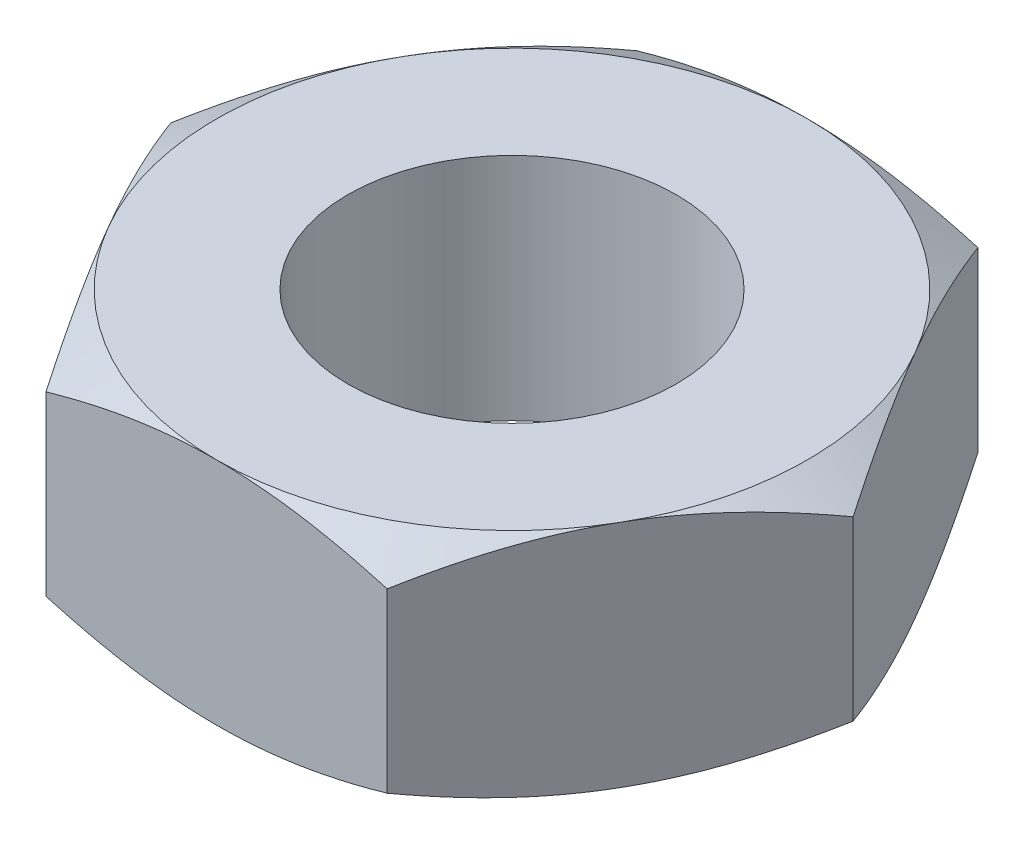
SolidWorks part; units mm, degrees
ref_plane "Front Plane" through (0, 0, 0) normal (0, 0, 1) x (1, 0, 0)
ref_plane "Top Plane" through (0, 0, 0) normal (0, 1, 0) x (1, 0, 0)
ref_plane "Right Plane" through (0, 0, 0) normal (1, 0, 0) x (0, 0, -1)
sketch "Sketch3" plane through (0, 0, 0) normal (0, 1, 0) x (1, 0, 0)
  line L1 (25.9808, 0) -> (12.9904, 22.5)
  line L2 (12.9904, 22.5) -> (-12.9904, 22.5)
  line L3 (-12.9904, 22.5) -> (-25.9808, 0)
  line L4 (-25.9808, 0) -> (-12.9904, -22.5)
  line L5 (-12.9904, -22.5) -> (12.9904, -22.5)
  line L6 (12.9904, -22.5) -> (25.9808, 0)
  circle A0 centre (0, 0) radius 12.5
  circle A1 centre (0, 0) radius 22.5 construction
  dimension "D1" = 45
  dimension "3" = 25
extrude "Boss-Extrude1" add sketch "Sketch3" along normal mid plane 17.5
sketch "Sketch4" plane through (0, -8.75, 0) normal (0, -1, 0) x (1, 0, 0)
  circle A0 centre (0, 0) radius 22.5
  dimension "D1" = 45
extrude "Cut-Extrude1" cut sketch "Sketch4" against normal blind 2 draft 60 flip side to cut
mirror "Mirror1" about plane through (0, 0, 0) normal (0, 1, 0) of "Cut-Extrude1"
